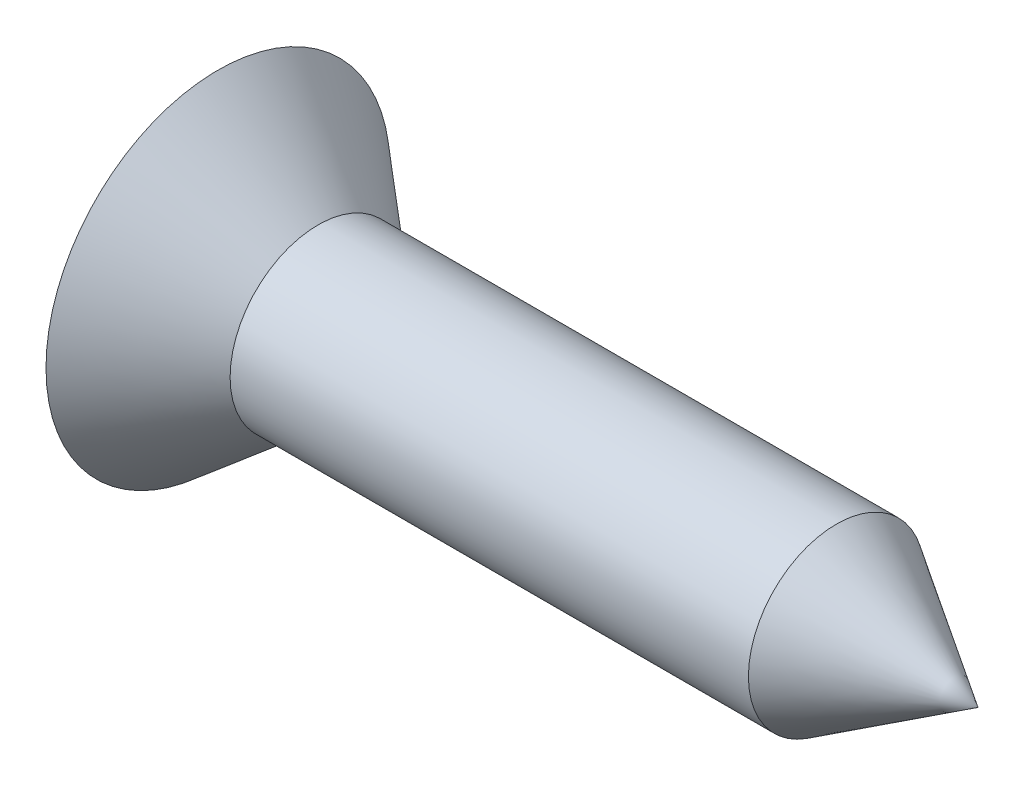
SolidWorks part; units mm, degrees
ref_plane "Front Plane" through (0, 0, 0) normal (0, 0, 1) x (1, 0, 0)
ref_plane "Top Plane" through (0, 0, 0) normal (0, 1, 0) x (1, 0, 0)
ref_plane "Right Plane" through (0, 0, 0) normal (1, 0, 0) x (0, 0, -1)
sketch "Skica1" plane through (0, 0, 0) normal (0, 0, 1) x (1, 0, 0)
  line L0 (0, 0) -> (10.0172, 0) construction
  line L1 (0, 0) -> (0, 2.15)
  line L2 (0, 2.15) -> (1.2513, 1.1)
  line L3 (1.2513, 1.1) -> (7.73, 1.1)
  line L4 (7.73, 1.1) -> (9.5, 0)
  line L5 (9.5, 0) -> (0, 0)
  dimension "D1" = 9.5
  dimension "D2" = 40
  dimension "D3" = 2.15
  dimension "D4" = 1.1
revolve "Rotovat1" add sketch "Skica1" angle 360 about L0
